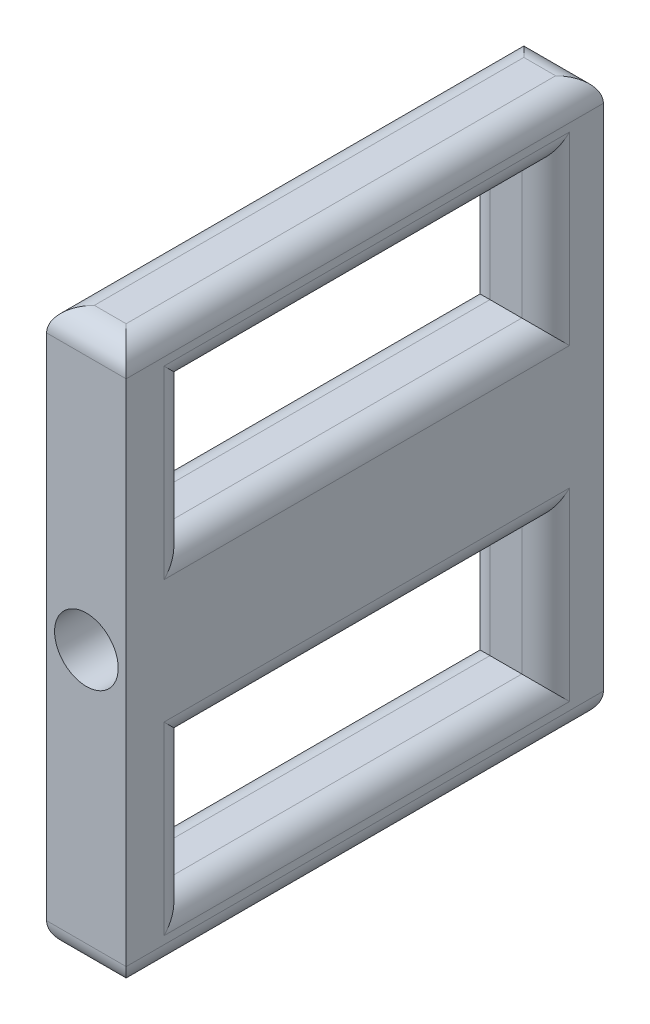
SolidWorks part; units mm, degrees
ref_plane "前视" through (0, 0, 0) normal (0, 0, 1) x (1, 0, 0)
ref_plane "上视" through (0, 0, 0) normal (0, 1, 0) x (1, 0, 0)
ref_plane "右视" through (0, 0, 0) normal (1, 0, 0) x (0, 0, -1)
sketch "草图1" plane through (0, 0, 0) normal (0, 0, 1) x (1, 0, 0)
  line L0 (0, 25.4568) -> (0, -44.5432)
  line L1 (0, 25.4568) -> (10, 25.4568)
  line L2 (10, 25.4568) -> (10, -44.5432)
  line L3 (10, -44.5432) -> (0, -44.5432)
  line L4 (-19.0759, -9.5432) -> (30.7654, -9.5432) construction
  line L5 (5, 9.4757) -> (5, -26.5069) construction
  circle A0 centre (5, -9.5432) radius 4
  dimension "D1" = 5
extrude "凸台-拉伸1" add sketch "草图1" along normal blind 60
sketch "草图2" plane through (10, 0, 0) normal (1, 0, 0) x (0, 0, -1)
  line L0 (-73.7873, -9.5432) -> (18.41, -9.5432) construction
  line L1 (-7.2577, -37.5539) -> (-7.2577, -20.2946)
  line L2 (-52.25, 18.4676) -> (-7.2577, 18.4676)
  line L3 (-52.25, 18.4676) -> (-52.25, 1.2082)
  line L4 (-52.25, 1.2082) -> (-7.2577, 1.2082)
  line L5 (-7.2577, 18.4676) -> (-7.2577, 1.2082)
  line L6 (-52.25, -20.2946) -> (-7.2577, -20.2946)
  line L7 (-52.25, -37.5539) -> (-7.2577, -37.5539)
  line L8 (-52.25, -37.5539) -> (-52.25, -20.2946)
extrude "切除-拉伸1" cut sketch "草图2" against normal through all contours L8 L7 L1 L6 | L3 L4 L5 L2
fillet "圆角1" radius 3 24 edges at (0, -37.5539, 29.7539) (10, -37.5539, 29.7539) (0, -28.9243, 7.2577) (10, -28.9243, 7.2577) (0, -20.2946, 29.7539) (10, -20.2946, 29.7539) (10, -28.9243, 52.25) (0, -28.9243, 52.25) (0, 9.8379, 52.25) (10, 9.8379, 52.25) (0, 9.8379, 7.2577) (10, 9.8379, 7.2577) (0, 1.2082, 29.7539) (0, 18.4676, 29.7539) (10, 18.4676, 29.7539) (10, 1.2082, 29.7539) (5, 25.4568, 60) (5, 25.4568, 0) (10, 25.4568, 30) (0, 25.4568, 30) (5, -44.5432, 0) (5, -44.5432, 60) (0, -44.5432, 30) (10, -44.5432, 30)
